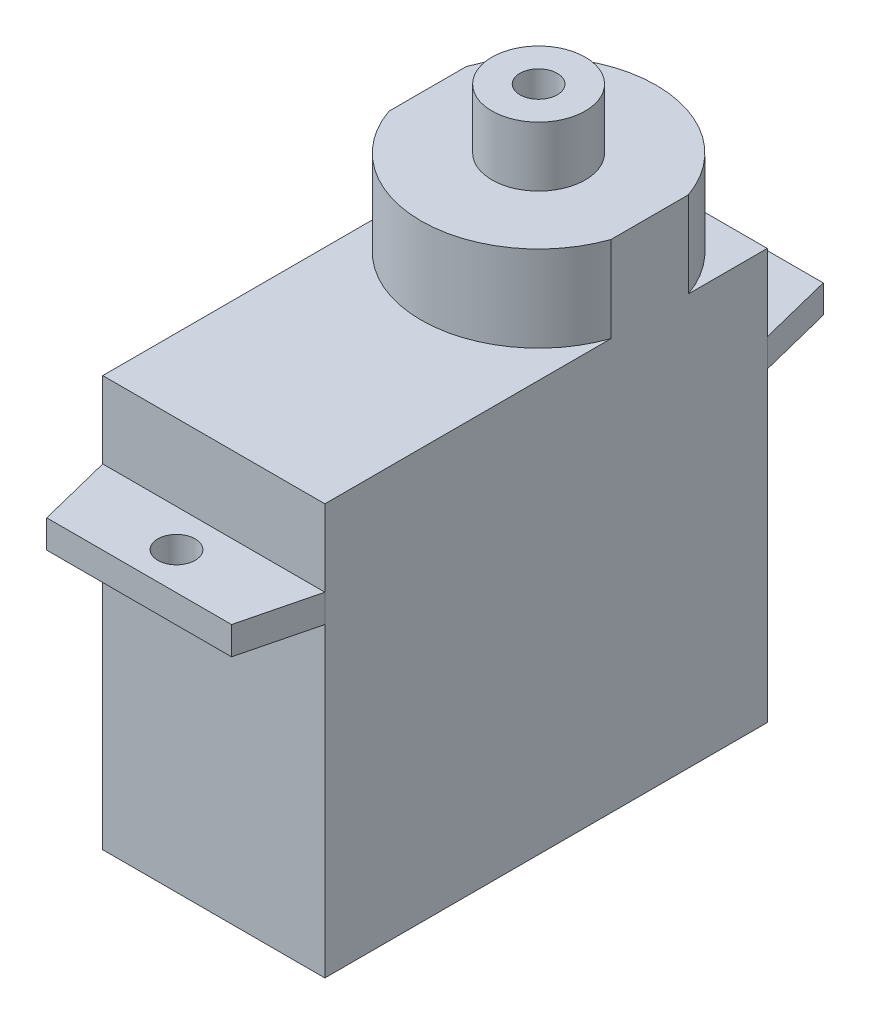
SolidWorks part; units mm, degrees
ref_plane "前视基准面" through (0, 0, 0) normal (0, 0, 1) x (1, 0, 0)
ref_plane "上视基准面" through (0, 0, 0) normal (0, 1, 0) x (1, 0, 0)
ref_plane "右视基准面" through (0, 0, 0) normal (1, 0, 0) x (0, 0, -1)
other "Configuration Table"
sketch "草图1" plane through (0, 0, 0) normal (0, 1, 0) x (1, 0, 0)
  line L1 (-5.95, 11.85) -> (5.95, 11.85)
  line L2 (-5.95, 11.85) -> (-5.95, -11.85)
  line L3 (-5.95, -11.85) -> (5.95, -11.85)
  line L4 (5.95, 11.85) -> (5.95, -11.85)
  line L5 (-5.95, 11.85) -> (5.95, -11.85) construction
  line L6 (-5.95, -11.85) -> (5.95, 11.85) construction
  point P4 (0, 0)
  dimension "D1" = 11.9
  dimension "D2" = 23.7
extrude "凸台-拉伸1" add sketch "草图1" along normal blind 16.4
sketch "草图2" plane through (0, 16.4, 0) normal (0, 1, 0) x (1, 0, 0)
  line L0 (0, 13.85) -> (0, 0) construction
  line L1 (0, 0) -> (0, -13.85) construction
  line L2 (-5.95, 11.85) -> (-4.95, 15.85)
  line L3 (-4.95, 15.85) -> (4.95, 15.85)
  line L4 (4.95, 15.85) -> (5.95, 11.85)
  line L5 (5.95, 11.85) -> (5.95, -11.85)
  line L6 (5.95, -11.85) -> (4.95, -15.85)
  line L7 (4.95, -15.85) -> (-4.95, -15.85)
  line L8 (-4.95, -15.85) -> (-5.95, -11.85)
  line L9 (-5.95, -11.85) -> (-5.95, 11.85)
  circle A0 centre (0, 13.85) radius 1
  circle A1 centre (0, -13.85) radius 1
  dimension "D1" = 2
  dimension "D2" = 27.7
  dimension "D3" = 31.7
  dimension "D4" = 1
extrude "凸台-拉伸2" add sketch "草图2" along normal blind 1.5
sketch "草图3" plane through (0, 17.9, 0) normal (0, 1, 0) x (1, 0, 0)
  line L1 (-5.95, 11.85) -> (5.95, 11.85)
  line L2 (-5.95, 11.85) -> (-5.95, -11.85)
  line L3 (-5.95, -11.85) -> (5.95, -11.85)
  line L4 (5.95, 11.85) -> (5.95, -11.85)
  line L5 (-5.95, 11.85) -> (5.95, -11.85) construction
  line L6 (-5.95, -11.85) -> (5.95, 11.85) construction
  point P4 (0, 0)
extrude "凸台-拉伸3" add sketch "草图3" along normal blind 4.1
sketch "草图4" plane through (0, 22, 0) normal (0, 1, 0) x (1, 0, 0)
  line L0 (0, 0) -> (0, 5.55) construction
  line L1 (5.95, 11.85) -> (-5.95, 11.85) construction
  line L2 (-5.95, 7.6206) -> (-5.95, 3.4794)
  line L3 (5.95, 7.6206) -> (5.95, 3.4794)
  line L4 (-5.95, 11.85) -> (-5.95, -11.85) construction
  line L5 (5.95, -11.85) -> (5.95, 11.85) construction
  arc A0 (5.95, 7.6206) -> (-5.95, 7.6206) centre (0, 5.55) ccw
  arc A1 (-5.95, 3.4794) -> (5.95, 3.4794) centre (0, 5.55) ccw
  dimension "D2" = 12.6
  dimension "D1" = 6.3
extrude "凸台-拉伸4" add sketch "草图4" along normal offset from surface (4.6 mm away) 26.6 up to face at (0, 0, 0)
sketch "草图5" plane through (0, 26.6, 0) normal (0, 1, 0) x (1, 0, 0)
  circle A0 centre (0, 5.55) radius 2.5
  arc A1 (5.95, 7.6206) -> (-5.95, 7.6206) centre (0, 5.55) ccw construction
  circle A2 centre (0, 5.55) radius 1
  dimension "D1" = 5
  dimension "D2" = 2
extrude "凸台-拉伸5" add sketch "草图5" along normal offset from surface (3.2 mm away) 29.8 up to face at (0, 0, 0)
